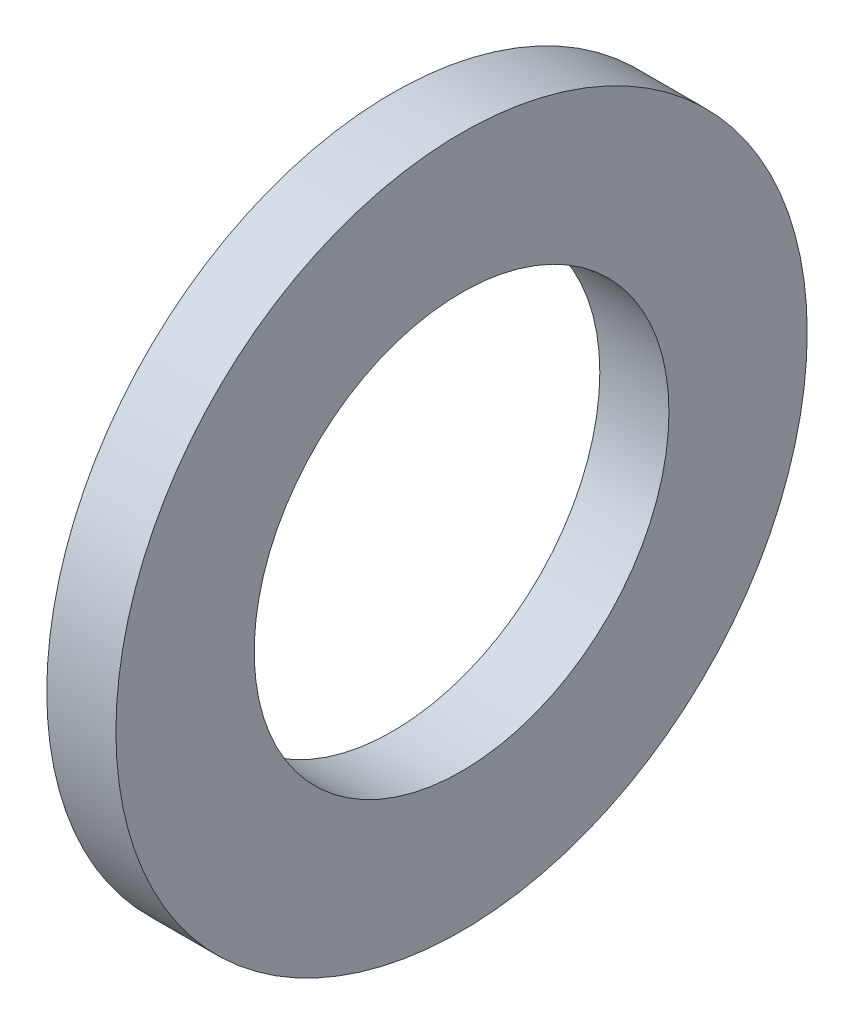
SolidWorks part; units mm, degrees
material "Plain Carbon Steel"
ref_plane "Front Plane" through (0, 0, 0) normal (0, 0, 1) x (1, 0, 0)
ref_plane "Top Plane" through (0, 0, 0) normal (0, 1, 0) x (1, 0, 0)
ref_plane "Right Plane" through (0, 0, 0) normal (1, 0, 0) x (0, 0, -1)
sketch "Sketch1" plane through (0, 0, 0) normal (1, 0, 0) x (0, 0, -1)
  circle A0 centre (0, 0) radius 9.525
  circle A1 centre (0, 0) radius 15.875
  dimension "D1" = 31.75
  dimension "D2" = 19.05
extrude "Boss-Extrude1" add sketch "Sketch1" along normal blind 3.175
